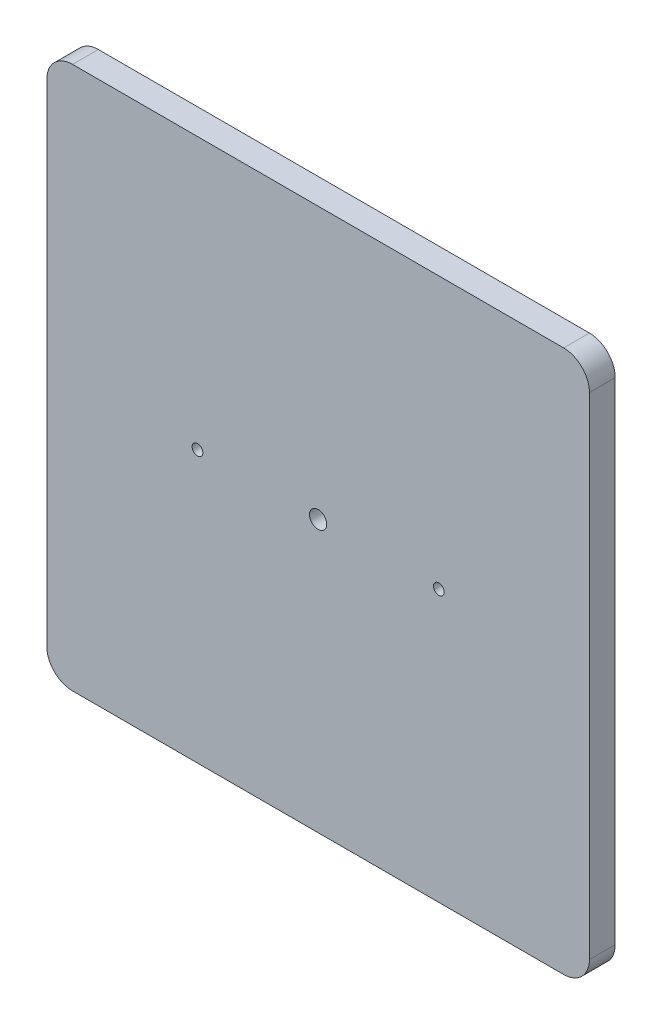
SolidWorks part; units mm, degrees
ref_plane "Front Plane" through (0, 0, 0) normal (0, 0, 1) x (1, 0, 0)
ref_plane "Top Plane" through (0, 0, 0) normal (0, 1, 0) x (1, 0, 0)
ref_plane "Right Plane" through (0, 0, 0) normal (1, 0, 0) x (0, 0, -1)
sketch "Baseplate" plane through (0, 0, 0) normal (0, 0, 1) x (1, 0, 0)
  line L2 (-100, 100) -> (100, 100)
  line L3 (-100, 100) -> (-100, -100)
  line L4 (-100, -100) -> (100, -100)
  line L5 (100, 100) -> (100, -100)
  line L6 (-100, 100) -> (100, -100) construction
  line L7 (-100, -100) -> (100, 100) construction
  point P2 (0, 0)
  dimension "D1" = 200
  dimension "D2" = 200
extrude "Boss-Extrude1" add sketch "Baseplate" along normal blind 9.5
sketch "LIDAR PLACEMENT" [suppressed] plane through (0, 0, 3) normal (0, 0, 1) x (1, 0, 0)
  circle A0 centre (0, 0) radius 51.65
  circle A1 centre (44.45, 0) radius 1.015
  dimension "D1" = 103.3
  dimension "2.03" = 2.03
  dimension "D2" = 44.45
fillet "Fillet1" radius 9.5 4 edges at (-100, -100, 4.75) (100, -100, 4.75) (100, 100, 4.75) (-100, 100, 4.75)
hole_wizard "1/4 Inch Bolt Hole" positions "Sketch7" profile "Sketch8" hole size "1/4" standard "ANSI Inch" end condition through all
sketch "Sketch7" plane through (0, 0, 0) normal (0, 0, -1) x (-1, 0, 0)
  point P0 (0, 0)
sketch "Sketch8" plane through (0, 0, 0) normal (1, 0, 0) x (0, 1, 0)
  line L0 (0, 0) -> (0, 9.5)
  line L1 (0, 9.5) -> (3.175, 9.5)
  line L2 (3.175, 9.5) -> (3.175, 0.635)
  line L3 (3.175, 0.635) -> (3.81, 0)
  line L5 (3.81, 0) -> (0, 0)
  line L6 (-3.175, 0.635) -> (-3.81, 0) construction
  line L11 (0, -6.35) -> (0, 107.95) construction
  dimension "Thru Hole Dia." = 6.35
  dimension "Thru Hole Depth" = 9.5
  dimension "Near C'Sink Dia." = 7.62
  dimension "Near C'Sink Angle" = 90
hole_wizard "5/32 Dowel Hole" positions "Sketch13" profile "Sketch14" hole size "5/32" standard "ANSI Inch" end condition through all
sketch "Sketch13" plane through (0, 0, 0) normal (0, 0, -1) x (-1, 0, 0)
  point P0 (-44.5, 0)
  point P2 (44.45, 0)
  dimension "D1" = 44.45
  dimension "D2" = 44.5
sketch "Sketch14" plane through (44.5, 0, 0) normal (1, 0, 0) x (0, 1, 0)
  line L0 (0, 0) -> (0, 9.5)
  line L1 (0, 9.5) -> (1.9844, 9.5)
  line L2 (1.9844, 9.5) -> (1.9844, 0.5328)
  line L3 (1.9844, 0.5328) -> (2.6194, 0)
  line L5 (2.6194, 0) -> (0, 0)
  line L6 (-1.9844, 0.5328) -> (-2.6194, 0) construction
  line L11 (0, -6.35) -> (0, 107.95) construction
  dimension "Thru Hole Dia." = 3.9688
  dimension "Thru Hole Depth" = 9.5
  dimension "Near C'Sink Dia." = 5.2387
  dimension "Near C'Sink Angle" = 100
